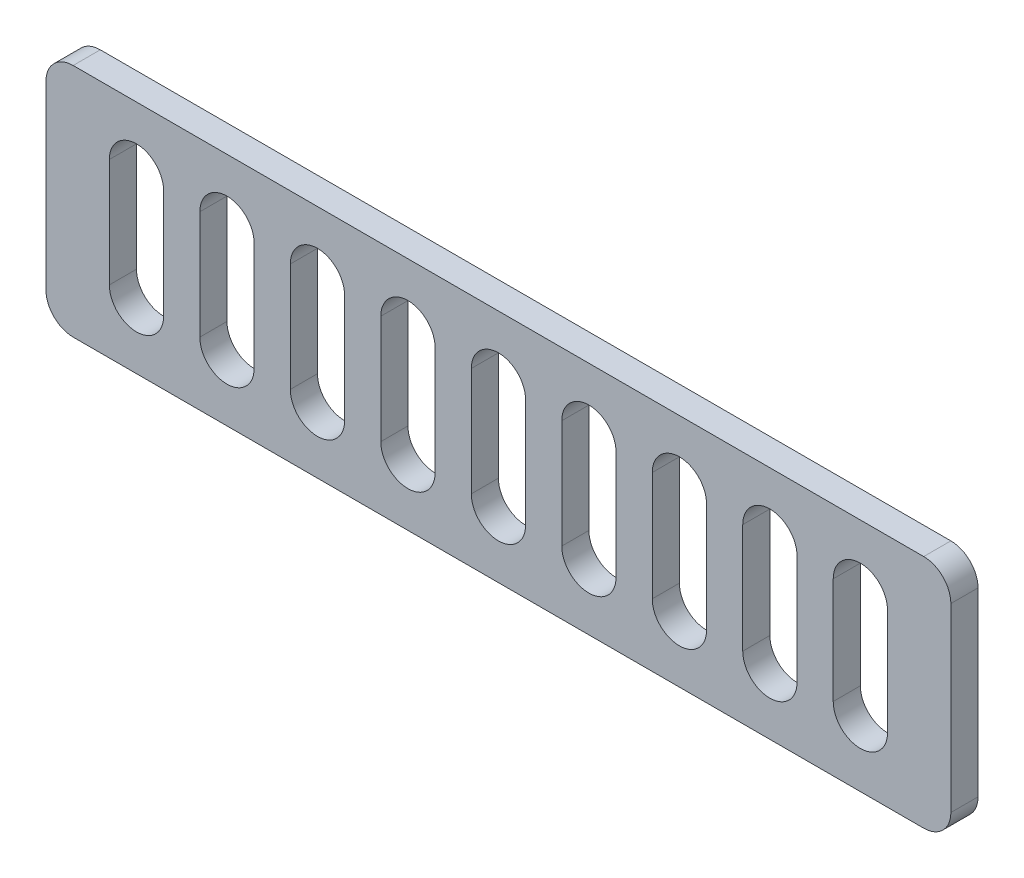
SolidWorks part; units mm, degrees
material "2014-T4"
ref_plane "Front Plane" through (0, 0, 0) normal (0, 0, 1) x (1, 0, 0)
ref_plane "Top Plane" through (0, 0, 0) normal (0, 1, 0) x (1, 0, 0)
ref_plane "Right Plane" through (0, 0, 0) normal (1, 0, 0) x (0, 0, -1)
sketch "Sketch1" plane through (0, 0, 0) normal (0, 0, 1) x (1, 0, 0)
  line L0 (-69.4989, -88.401) -> (-69.4989, -100.401) construction
  line L1 (-66.4989, -88.401) -> (-66.4989, -100.401)
  line L2 (-72.4989, -88.401) -> (-72.4989, -100.401)
  line L3 (-59.4989, -88.401) -> (-59.4989, -100.401) construction
  line L4 (-119.4989, -107.401) -> (-19.4989, -107.401)
  line L5 (-19.4989, -81.401) -> (-19.4989, -107.401)
  line L6 (-119.4989, -81.401) -> (-19.4989, -81.401)
  line L7 (-119.4989, -81.401) -> (-119.4989, -107.401)
  line L8 (-109.4989, -88.401) -> (-109.4989, -100.401) construction
  line L9 (-106.4989, -88.401) -> (-106.4989, -100.401)
  line L10 (-112.4989, -88.401) -> (-112.4989, -100.401)
  line L11 (-99.4989, -88.401) -> (-99.4989, -100.401) construction
  line L12 (-96.4989, -88.401) -> (-96.4989, -100.401)
  line L13 (-102.4989, -88.401) -> (-102.4989, -100.401)
  line L14 (-49.4989, -88.3556) -> (-49.4989, -100.4465) construction
  line L17 (-89.4989, -88.401) -> (-89.4989, -100.401) construction
  line L18 (-86.4989, -88.401) -> (-86.4989, -100.401)
  line L19 (-92.4989, -88.401) -> (-92.4989, -100.401)
  line L20 (-79.4989, -88.401) -> (-79.4989, -100.401) construction
  line L21 (-76.4989, -88.401) -> (-76.4989, -100.401)
  line L22 (-82.4989, -88.401) -> (-82.4989, -100.401)
  line L23 (-56.4989, -88.401) -> (-56.4989, -100.401)
  line L26 (-62.4989, -88.401) -> (-62.4989, -100.401)
  line L27 (-13.6484, -94.401) -> (-124.7235, -94.401) construction
  line L28 (-46.4989, -88.3556) -> (-46.4989, -100.4465)
  line L29 (-52.4989, -88.3556) -> (-52.4989, -100.4465)
  line L30 (-39.4989, -88.3465) -> (-39.4989, -100.4555) construction
  line L31 (-36.4989, -88.3465) -> (-36.4989, -100.4555)
  line L32 (-42.4989, -88.3465) -> (-42.4989, -100.4555)
  line L33 (-29.4989, -88.5311) -> (-29.4989, -100.271) construction
  line L34 (-26.4989, -88.5311) -> (-26.4989, -100.271)
  line L35 (-32.4989, -88.5311) -> (-32.4989, -100.271)
  arc A0 (-106.4989, -88.401) -> (-112.4989, -88.401) centre (-109.4989, -88.401) ccw
  arc A1 (-112.4989, -100.401) -> (-106.4989, -100.401) centre (-109.4989, -100.401) ccw
  arc A2 (-96.4989, -88.401) -> (-102.4989, -88.401) centre (-99.4989, -88.401) ccw
  arc A3 (-102.4989, -100.401) -> (-96.4989, -100.401) centre (-99.4989, -100.401) ccw
  arc A6 (-86.4989, -88.401) -> (-92.4989, -88.401) centre (-89.4989, -88.401) ccw
  arc A7 (-92.4989, -100.401) -> (-86.4989, -100.401) centre (-89.4989, -100.401) ccw
  arc A8 (-76.4989, -88.401) -> (-82.4989, -88.401) centre (-79.4989, -88.401) ccw
  arc A9 (-82.4989, -100.401) -> (-76.4989, -100.401) centre (-79.4989, -100.401) ccw
  arc A12 (-66.4989, -88.401) -> (-72.4989, -88.401) centre (-69.4989, -88.401) ccw
  arc A13 (-72.4989, -100.401) -> (-66.4989, -100.401) centre (-69.4989, -100.401) ccw
  arc A14 (-56.4989, -88.401) -> (-62.4989, -88.401) centre (-59.4989, -88.401) ccw
  arc A15 (-62.4989, -100.401) -> (-56.4989, -100.401) centre (-59.4989, -100.401) ccw
  arc A16 (-46.4989, -88.3556) -> (-52.4989, -88.3556) centre (-49.4989, -88.3556) ccw
  arc A17 (-52.4989, -100.4465) -> (-46.4989, -100.4465) centre (-49.4989, -100.4465) ccw
  arc A18 (-36.4989, -88.3465) -> (-42.4989, -88.3465) centre (-39.4989, -88.3465) ccw
  arc A19 (-42.4989, -100.4555) -> (-36.4989, -100.4555) centre (-39.4989, -100.4555) ccw
  arc A20 (-26.4989, -88.5311) -> (-32.4989, -88.5311) centre (-29.4989, -88.5311) ccw
  arc A21 (-32.4989, -100.271) -> (-26.4989, -100.271) centre (-29.4989, -100.271) ccw
  point P6 (-109.4989, -94.401)
  point P13 (-99.4989, -94.401)
  point P20 (-49.4989, -94.401)
  point P27 (-89.4989, -94.401)
  point P34 (-79.4989, -94.401)
  point P41 (-69.4989, -94.401)
  point P48 (-59.4989, -94.401)
  point P63 (-39.4989, -94.401)
  point P70 (-29.4989, -94.401)
  dimension "D10" = 3
  dimension "D1" = 13
  dimension "D2" = 26
  dimension "D3" = 12
  dimension "D4" = 10
  dimension "D5" = 10
  dimension "D6" = 10
  dimension "D7" = 10
  dimension "D8" = 10
  dimension "D9" = 10
  dimension "D11" = 100
  dimension "D12" = 10
  dimension "D13" = 10
  dimension "D14" = 10
extrude "Boss-Extrude1" add sketch "Sketch1" against normal blind 3
fillet "Fillet1" radius 3 4 edges at (-119.4989, -107.401, -1.5) (-19.4989, -107.401, -1.5) (-19.4989, -81.401, -1.5) (-119.4989, -81.401, -1.5)
